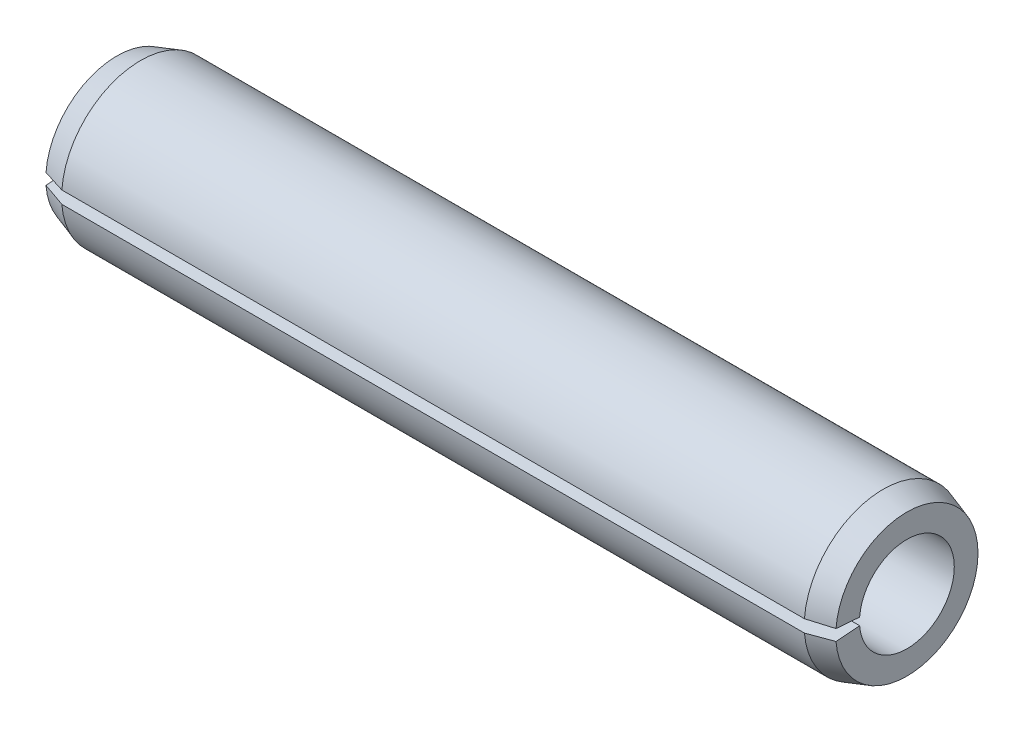
SolidWorks part; units mm, degrees
ref_plane "Plane1" through (0, 0, 0) normal (0, 0, 1) x (1, 0, 0)
ref_plane "Plane2" through (0, 0, 0) normal (0, 1, 0) x (1, 0, 0)
ref_plane "Plane3" through (0, 0, 0) normal (1, 0, 0) x (0, 0, -1)
other "Configuration Table"
sketch "BodySke" plane through (0, 0, 0) normal (0, 0, 1) x (1, 0, 0)
  line L0 (-9.525, 0) -> (111.125, 0) construction
  line L1 (0, 0.6) -> (10, 0.6)
  line L2 (10, 0.6) -> (10, 0.9)
  line L3 (10, 0.9) -> (9.7, 1)
  line L4 (9.7, 1) -> (0.3, 1)
  line L5 (0.3, 1) -> (0, 0.9)
  line L7 (0, 0.9) -> (0, 0.6)
  dimension "Diameter" = 2
  dimension "Thickness" = 0.4
  dimension "Length" = 10
  dimension "Chamfer_len" = 0.3
  dimension "D1" = 1.8
  dimension "D2" = 1.8
  dimension "D3" = 0.3
revolve "Body" add sketch "BodySke" angle 360 about L0
sketch "GapSke" plane through (0, 0, 0) normal (-1, 0, 0) x (0, -1, 0)
  line L0 (0, 0) -> (0.08, 1.0169)
  line L1 (0, -3.175) -> (0, 12.7) construction
  line L2 (0, 0) -> (-0.08, 1.0169)
  arc A0 (0.08, 1.0169) -> (-0.08, 1.0169) centre (0, 0) ccw
  dimension "Gap_ang" = 9
  dimension "D1" = 1.02
extrude "Gap" cut sketch "GapSke" against normal through all
equation "\"D1@GapSke\" = \"Diameter@BodySke\" * 0.51"
equation "\"D1@BodySke\" = \"Diameter@BodySke\" -  ( \"Thickness@BodySke\" / 2 ) "
equation "\"D2@BodySke\" = \"D1@BodySke\""
equation "\"D3@BodySke\" = \"Chamfer_len@BodySke\""
